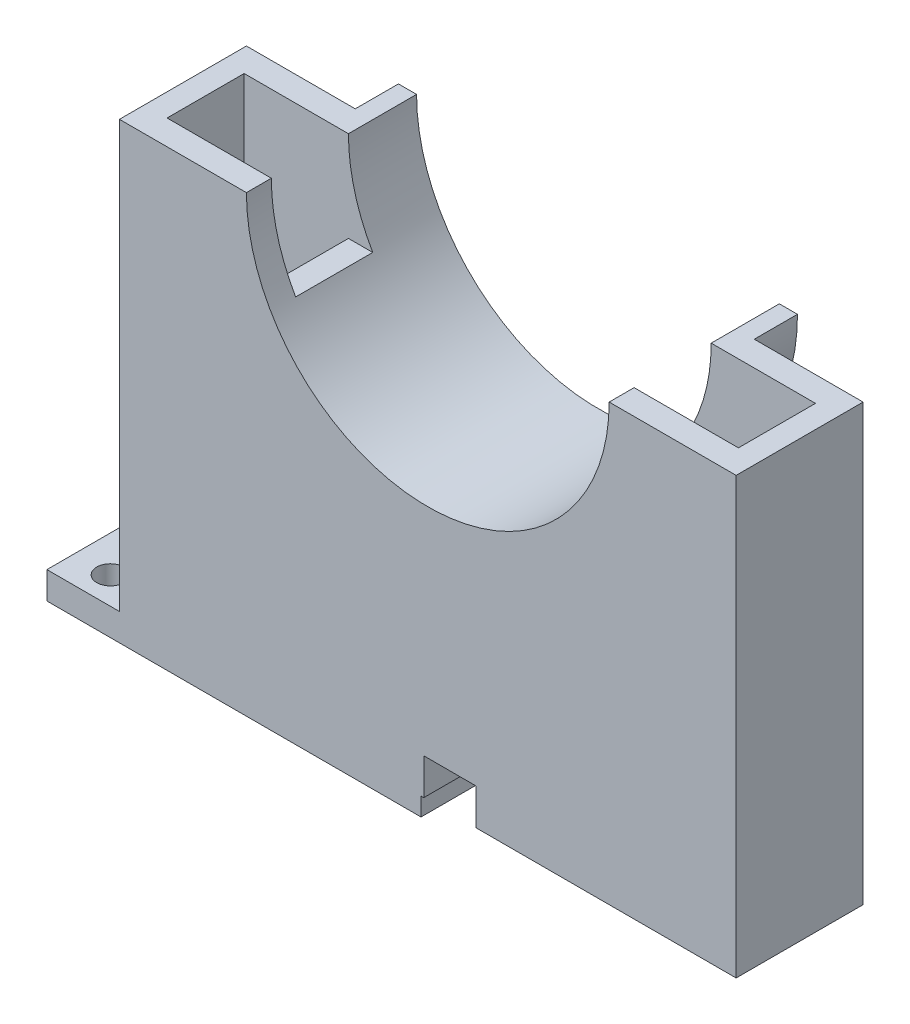
SolidWorks part; units mm, degrees
ref_plane "Front Plane" through (0, 0, 0) normal (0, 0, 1) x (1, 0, 0)
ref_plane "Top Plane" through (0, 0, 0) normal (0, 1, 0) x (1, 0, 0)
ref_plane "Right Plane" through (0, 0, 0) normal (1, 0, 0) x (0, 0, -1)
sketch "Sketch1" plane through (0, 0, 0) normal (0, 0, 1) x (1, 0, 0)
  line L0 (0, 0) -> (0, 3)
  line L1 (0, 3) -> (8, 3)
  line L2 (0, 0) -> (76, 0)
  line L3 (76, 0) -> (76, 50)
  line L4 (8, 3) -> (8, 50)
  line L5 (8, 50) -> (22, 50)
  line L6 (76, 50) -> (62, 50)
  arc A1 (62, 50) -> (22, 50) centre (42, 50) cw
  dimension "D1" = 14
  dimension "D2" = 20
  dimension "D3" = 3
  dimension "D4" = 50
  dimension "D5" = 8
extrude "Boss-Extrude1" add sketch "Sketch1" along normal blind 14
sketch "Sketch2" plane through (0, 0, 0) normal (0, -1, 0) x (1, 0, 0)
  line L0 (42, 14) -> (42, 0) construction
  line L1 (0, 14) -> (76, 14) construction
  line L2 (0, 0) -> (76, 0) construction
  line L3 (62, 14) -> (22, 14) construction
  line L4 (73.5, 11.25) -> (62, 11.25)
  line L5 (62, 11.25) -> (62, 2.75)
  line L6 (62, 2.75) -> (73.5, 2.75)
  line L7 (73.5, 2.75) -> (73.5, 11.25)
  line L10 (76, 14) -> (76, 0) construction
  line L11 (22, 2.75) -> (10.5, 2.75)
  line L12 (22, 11.25) -> (22, 2.75)
  line L13 (10.5, 11.25) -> (22, 11.25)
  line L14 (10.5, 2.75) -> (10.5, 11.25)
  point P14 (76, 7)
  point P15 (73.5, 7)
  dimension "D1" = 11.5
  dimension "D2" = 8.5
  dimension "D3" = 2.5
extrude "Cut-Extrude1" cut sketch "Sketch2" against normal up to surface (50 mm away) up to face at (15, 50, 7)
sketch "Sketch3" plane through (0, 3, 0) normal (0, 1, 0) x (1, 0, 0)
  line L0 (4, -3) -> (4, -11) construction
  line L1 (0, -14) -> (0, 0) construction
  line L4 (8, -14) -> (0, -14) construction
  circle A0 centre (4, -3) radius 1.5
  circle A1 centre (4, -11) radius 1.5
  point P7 (4, -14)
  point P10 (0, -7)
  point P11 (4, -7)
  dimension "D1" = 3
  dimension "D2" = 3
  dimension "D3" = 8
extrude "screw holes" cut sketch "Sketch3" against normal up to surface (3 mm away) up to face at (67.75, 0, 7)
sketch "Sketch4" plane through (0, 50, 0) normal (0, 1, 0) x (1, 0, 0)
  line L0 (8, -14) -> (76, -14) construction
  line L1 (10.5, -11.25) -> (73.5, -11.25)
  line L5 (73.5, -2.75) -> (73.5, -11.25)
  line L9 (10.5, -2.75) -> (10.5, -11.25)
  line L10 (10.5, -2.75) -> (73.5, -2.75)
  line L11 (10.5, -2.75) -> (10.5, -11.25) construction
extrude "Cut-Extrude2" cut sketch "Sketch4" against normal blind 10
sketch "Sketch5" plane through (0, 0, 0) normal (0, 0, -1) x (-1, 0, 0)
  line L0 (-76, 0) -> (-76, 2)
  line L1 (-76, 0) -> (-76, 50) construction
  line L2 (-76, 2) -> (-41.255, 2)
  line L3 (-41.255, 2) -> (-41.255, 0)
  line L4 (0, 0) -> (-76, 0) construction
  line L5 (-41.255, 0) -> (-76, 0)
  arc A1 (-62, 50) -> (-22, 50) centre (-42, 50) ccw construction
  point P12 (-42, 30)
  dimension "D1" = 2
  dimension "D2" = 0.745
extrude "Cut-Extrude3" cut sketch "Sketch5" against normal up to surface (14 mm away) up to face at (31.5, 23.25, 14)
sketch "Sketch6" plane through (0, 0, 14) normal (0, 0, 1) x (1, 0, 0)
  line L0 (41.555, 2) -> (47.305, 2)
  line L2 (76, 2) -> (41.255, 2) construction
  line L3 (41.255, 2) -> (41.255, 0) construction
  line L4 (47.305, 2) -> (47.305, 6)
  line L5 (47.305, 6) -> (41.555, 6)
  line L6 (41.555, 6) -> (41.555, 2)
  point P6 (44.43, 2)
  dimension "D1" = 5.75
  dimension "D2" = 3.175
  dimension "D3" = 4
extrude "Cut-Extrude4" cut sketch "Sketch6" against normal up to surface (14 mm away) up to face at (33.451, 19, 0)
sketch "Sketch7" plane through (0, 0, 14) normal (0, 0, 1) x (1, 0, 0)
  line L0 (22, 50) -> (20, 50)
  line L1 (22, 50) -> (8, 50) construction
  line L2 (62, 50) -> (64, 50)
  line L3 (76, 50) -> (62, 50) construction
  arc A0 (22, 50) -> (62, 50) centre (42, 50) ccw
  arc A1 (20, 50) -> (64, 50) centre (42, 50) ccw
  dimension "D1" = 2
  dimension "D2" = 2
extrude "Boss-Extrude2" add sketch "Sketch7" against normal blind 4.7625 from surface at -14 starting at face at (36.5879, 14.7143, 0)
